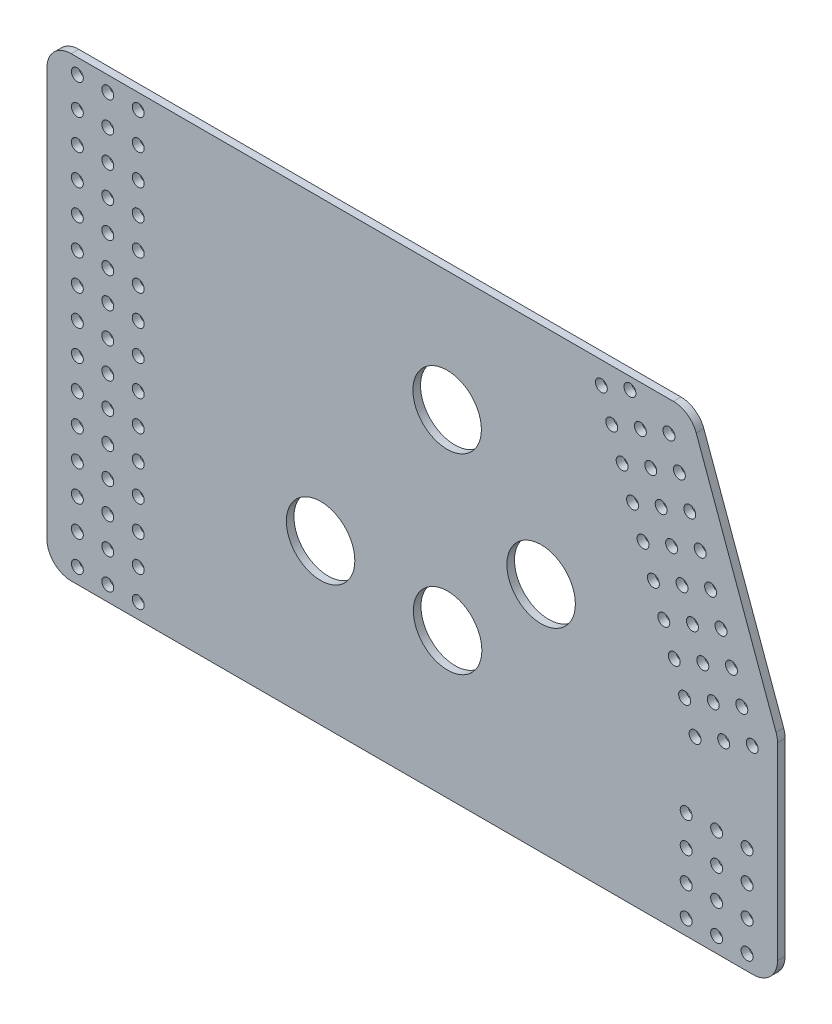
SolidWorks part; units mm, degrees
ref_plane "Front Plane" through (0, 0, 0) normal (0, 0, 1) x (1, 0, 0)
ref_plane "Top Plane" through (0, 0, 0) normal (0, 1, 0) x (1, 0, 0)
ref_plane "Right Plane" through (0, 0, 0) normal (1, 0, 0) x (0, 0, -1)
sketch "Sketch2" plane through (0, 0, 0) normal (0, 0, 1) x (1, 0, 0)
  line L0 (-62.0347, 275.0603) -> (206.4353, 275.0603)
  line L3 (206.4353, 275.0603) -> (242.7653, 175.2445)
  line L4 (242.7653, 175.2445) -> (242.7653, 84.5603)
  line L6 (242.7653, 84.5603) -> (-62.0347, 84.5603)
  line L7 (-62.0347, 84.5603) -> (-62.0347, 275.0603)
  line L8 (-49.3347, 268.7103) -> (-36.6347, 268.7103) construction
  line L9 (-49.3347, 268.7103) -> (-49.3347, 256.0103) construction
  line L10 (105.1393, -854.8604) -> (105.1393, 49145.1396) construction
  line L11 (169.2687, 265.7779) -> (173.6123, 253.8438) construction
  line L12 (204.6653, 129.0103) -> (204.6653, 116.3103) construction
  line L15 (-894.8607, 145.1396) -> (49105.1393, 145.1396) construction
  circle A2 centre (-49.3347, 268.7103) radius 2.4892
  circle A3 centre (-49.3347, 90.9103) radius 2.4892
  circle A4 centre (-36.6347, 268.7103) radius 2.4892
  circle A5 centre (-23.9347, 268.7103) radius 2.4892
  circle A6 centre (-36.6347, 256.0103) radius 2.4892
  circle A7 centre (-23.9347, 256.0103) radius 2.4892
  circle A8 centre (-36.6347, 243.3103) radius 2.4892
  circle A9 centre (-23.9347, 243.3103) radius 2.4892
  circle A10 centre (-36.6347, 230.6103) radius 2.4892
  circle A11 centre (-23.9347, 230.6103) radius 2.4892
  circle A12 centre (-36.6347, 217.9103) radius 2.4892
  circle A13 centre (-23.9347, 217.9103) radius 2.4892
  circle A14 centre (-36.6347, 205.2103) radius 2.4892
  circle A15 centre (-23.9347, 205.2103) radius 2.4892
  circle A16 centre (-36.6347, 192.5103) radius 2.4892
  circle A17 centre (-23.9347, 192.5103) radius 2.4892
  circle A18 centre (-36.6347, 179.8103) radius 2.4892
  circle A19 centre (-23.9347, 179.8103) radius 2.4892
  circle A20 centre (-36.6347, 167.1103) radius 2.4892
  circle A21 centre (-23.9347, 167.1103) radius 2.4892
  circle A22 centre (-36.6347, 154.4103) radius 2.4892
  circle A23 centre (-23.9347, 154.4103) radius 2.4892
  circle A24 centre (-36.6347, 141.7103) radius 2.4892
  circle A25 centre (-23.9347, 141.7103) radius 2.4892
  circle A26 centre (-36.6347, 129.0103) radius 2.4892
  circle A27 centre (-23.9347, 129.0103) radius 2.4892
  circle A28 centre (-36.6347, 116.3103) radius 2.4892
  circle A29 centre (-23.9347, 116.3103) radius 2.4892
  circle A30 centre (-36.6347, 103.6103) radius 2.4892
  circle A31 centre (-23.9347, 103.6103) radius 2.4892
  circle A32 centre (-36.6347, 90.9103) radius 2.4892
  circle A33 centre (-23.9347, 90.9103) radius 2.4892
  circle A34 centre (-49.3347, 256.0103) radius 2.4892
  circle A35 centre (-49.3347, 243.3103) radius 2.4892
  circle A36 centre (-49.3347, 230.6103) radius 2.4892
  circle A37 centre (-49.3347, 217.9103) radius 2.4892
  circle A38 centre (-49.3347, 205.2103) radius 2.4892
  circle A39 centre (-49.3347, 192.5103) radius 2.4892
  circle A40 centre (-49.3347, 179.8103) radius 2.4892
  circle A41 centre (-49.3347, 167.1103) radius 2.4892
  circle A42 centre (-49.3347, 154.4103) radius 2.4892
  circle A43 centre (-49.3347, 141.7103) radius 2.4892
  circle A44 centre (-49.3347, 129.0103) radius 2.4892
  circle A45 centre (-49.3347, 116.3103) radius 2.4892
  circle A46 centre (-49.3347, 103.6103) radius 2.4892
  circle A47 centre (-49.3347, 90.9103) radius 2.4892
  circle A48 centre (169.2687, 265.7779) radius 2.4892
  circle A49 centre (181.2028, 270.1215) radius 2.4892
  circle A50 centre (197.4805, 262.5311) radius 2.4892
  circle A51 centre (173.6123, 253.8438) radius 2.4892
  circle A52 centre (185.5464, 258.1874) radius 2.4892
  circle A53 centre (201.8242, 250.597) radius 2.4892
  circle A54 centre (177.956, 241.9097) radius 2.4892
  circle A55 centre (189.8901, 246.2533) radius 2.4892
  circle A56 centre (206.1678, 238.6629) radius 2.4892
  circle A57 centre (182.2996, 229.9756) radius 2.4892
  circle A58 centre (194.2337, 234.3192) radius 2.4892
  circle A59 centre (210.5115, 226.7288) radius 2.4892
  circle A60 centre (186.6433, 218.0415) radius 2.4892
  circle A61 centre (198.5774, 222.3851) radius 2.4892
  circle A62 centre (214.8551, 214.7947) radius 2.4892
  circle A63 centre (190.9869, 206.1074) radius 2.4892
  circle A64 centre (202.921, 210.451) radius 2.4892
  circle A65 centre (219.1988, 202.8606) radius 2.4892
  circle A66 centre (195.3306, 194.1733) radius 2.4892
  circle A67 centre (207.2647, 198.5169) radius 2.4892
  circle A68 centre (223.5424, 190.9265) radius 2.4892
  circle A69 centre (199.6743, 182.2392) radius 2.4892
  circle A70 centre (211.6083, 186.5828) radius 2.4892
  circle A71 centre (227.8861, 178.9924) radius 2.4892
  circle A72 centre (204.0179, 170.3051) radius 2.4892
  circle A73 centre (215.952, 174.6488) radius 2.4892
  circle A74 centre (232.2298, 167.0583) radius 2.4892
  circle A75 centre (208.3616, 158.371) radius 2.4892
  circle A76 centre (220.2957, 162.7147) radius 2.4892
  circle A78 centre (236.5734, 155.1242) radius 2.4892 [skipped]
  circle A79 centre (204.6653, 129.0103) radius 2.4892
  circle A80 centre (217.3653, 129.0103) radius 2.4892
  circle A81 centre (230.0653, 129.0103) radius 2.4892
  circle A82 centre (204.6653, 116.3103) radius 2.4892
  circle A83 centre (217.3653, 116.3103) radius 2.4892
  circle A84 centre (230.0653, 116.3103) radius 2.4892
  circle A85 centre (204.6653, 103.6103) radius 2.4892
  circle A86 centre (217.3653, 103.6103) radius 2.4892
  circle A87 centre (230.0653, 103.6103) radius 2.4892
  circle A88 centre (204.6653, 90.9103) radius 2.4892
  circle A89 centre (217.3653, 90.9103) radius 2.4892
  circle A90 centre (230.0653, 90.9103) radius 2.4892
  circle A92 centre (52.1422, 151.0564) radius 14.2875
  circle A94 centre (105.1393, 145.1396) radius 14.2875
  circle A95 centre (104.9447, 224.8273) radius 14.2875
  circle A96 centre (144.1424, 181.3926) radius 14.2875
  dimension "D1" = 4.9784
  dimension "D2" = 6.35
  dimension "D3" = 4.9784
  dimension "D10" = 4.9784
  dimension "D11" = 4.9784
  dimension "D12" = 4.9784
  dimension "D15" = 4.9784
  dimension "D16" = 4.9784
  dimension "D17" = 4.9784
  dimension "D21" = 28.575
  dimension "D22" = 28.575
  dimension "D23" = 28.575
  dimension "D24" = 28.575
  dimension "D4" = 12.7
  dimension "D5" = 3
  dimension "D7" = 12.7
  dimension "D8" = 12.7
  dimension "D9" = 6.35
  dimension "D14" = 12.7
  dimension "D19" = 12.7
  dimension "D6" = 15
  dimension "D13" = 10
  dimension "D18" = 4
extrude "Boss-Extrude1" add sketch "Sketch2" along normal blind 3.175 contours L7 L6 L4 L3 L0 A96 A95 A94 A92 A90 A89 A88 A87 A86 A85 A84 A83 A82 A81 A80 A79 A76 A75 A74 A73 A72 A71 A70
fillet "Fillet1" radius 10.16 5 edges at (-62.0347, 275.0603, 1.5875) (206.4353, 275.0603, 1.5875) (242.7653, 175.2445, 1.5875) (242.7653, 84.5603, 1.5875) (-62.0347, 84.5603, 1.5875)
